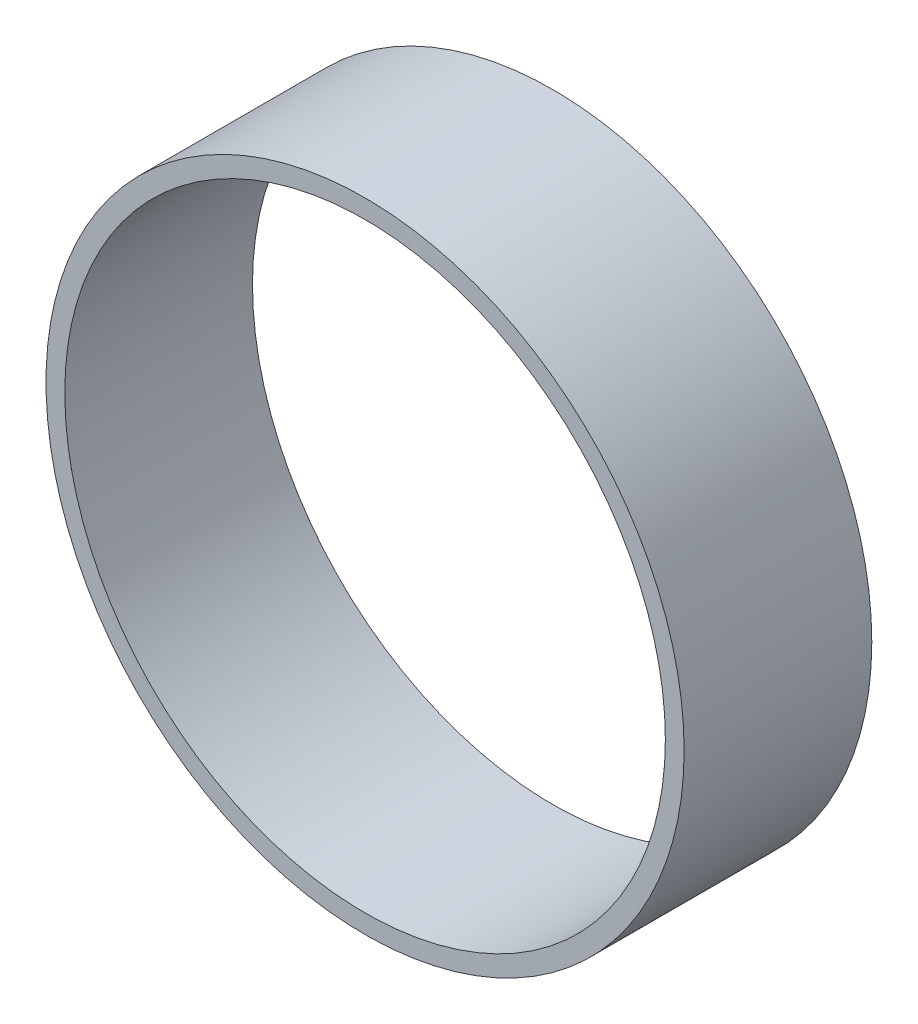
SolidWorks part; units mm, degrees
ref_plane "前视基准面" through (0, 0, 0) normal (0, 0, 1) x (1, 0, 0)
ref_plane "上视基准面" through (0, 0, 0) normal (0, 1, 0) x (1, 0, 0)
ref_plane "右视基准面" through (0, 0, 0) normal (1, 0, 0) x (0, 0, -1)
other "Configuration Table"
sketch "草图1" plane through (0, 0, 0) normal (0, 0, 1) x (1, 0, 0)
  circle A0 centre (0, 0) radius 8
  circle A1 centre (0, 0) radius 8.5
  dimension "D1" = 17
  dimension "D2" = 16
extrude "凸台-拉伸1" add sketch "草图1" along normal blind 5
